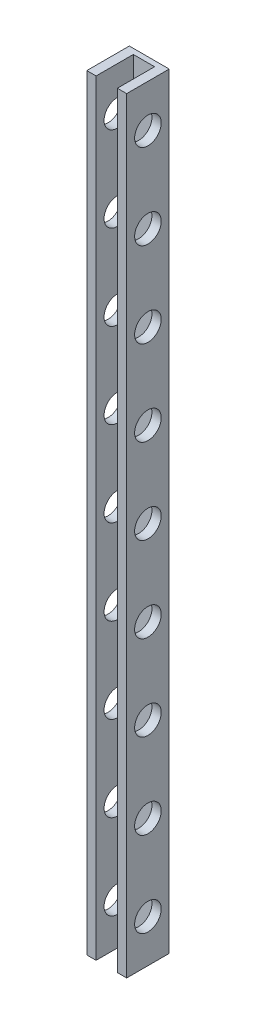
SolidWorks part; units mm, degrees
ref_plane "Plan de face" through (0, 0, 0) normal (0, 0, 1) x (1, 0, 0)
ref_plane "Plan de dessus" through (0, 0, 0) normal (0, 1, 0) x (1, 0, 0)
ref_plane "Plan de droite" through (0, 0, 0) normal (1, 0, 0) x (0, 0, -1)
sketch "Esquisse1" plane through (0, 0, 0) normal (0, 1, 0) x (1, 0, 0)
  line L0 (-2, -4) -> (-2, 3)
  line L1 (3.75, 4) -> (-3.75, 4)
  line L2 (3.75, 4) -> (3.75, -4)
  line L3 (3.75, -4) -> (2, -4)
  line L4 (-3.75, 4) -> (-3.75, -4)
  line L5 (3.75, 4) -> (-3.75, -4) construction
  line L6 (3.75, -4) -> (-3.75, 4) construction
  line L7 (-2, 3) -> (2, 3)
  line L8 (2, 3) -> (2, -4)
  line L9 (-2, 3) -> (2, -4) construction
  line L10 (0, -1.2247) -> (0, 2.1498) construction
  line L11 (-2, -4) -> (-3.75, -4)
  point P0 (0, 0)
  point P8 (0, -0.5)
  dimension "D1" = 7.5
  dimension "D2" = 8
  dimension "D3" = 1
  dimension "D4" = 4
extrude "Base" add sketch "Esquisse1" against normal blind 144
sketch "Esquisse2" plane through (-3.75, 0, 0) normal (-1, 0, 0) x (0, 0, 1)
  line L0 (0, 0) -> (0, -144) construction
  line L1 (-4, -144) -> (4, -144) construction
  line L3 (0, -5.5) -> (3.0778, -5.5) construction
  line L4 (-4, 0) -> (4, 0) construction
  circle A0 centre (0, -8) radius 2.5
  circle A1 centre (0, -24) radius 2.5
  circle A2 centre (0, -40) radius 2.5
  circle A3 centre (0, -56) radius 2.5
  circle A4 centre (0, -72) radius 2.5
  circle A5 centre (0, -88) radius 2.5
  circle A6 centre (0, -104) radius 2.5
  circle A7 centre (0, -120) radius 2.5
  circle A8 centre (0, -136) radius 2.5
  dimension "D1" = 5
  dimension "D2" = 5.5
  dimension "D3" = 9
extrude "Trou" cut sketch "Esquisse2" against normal through all
